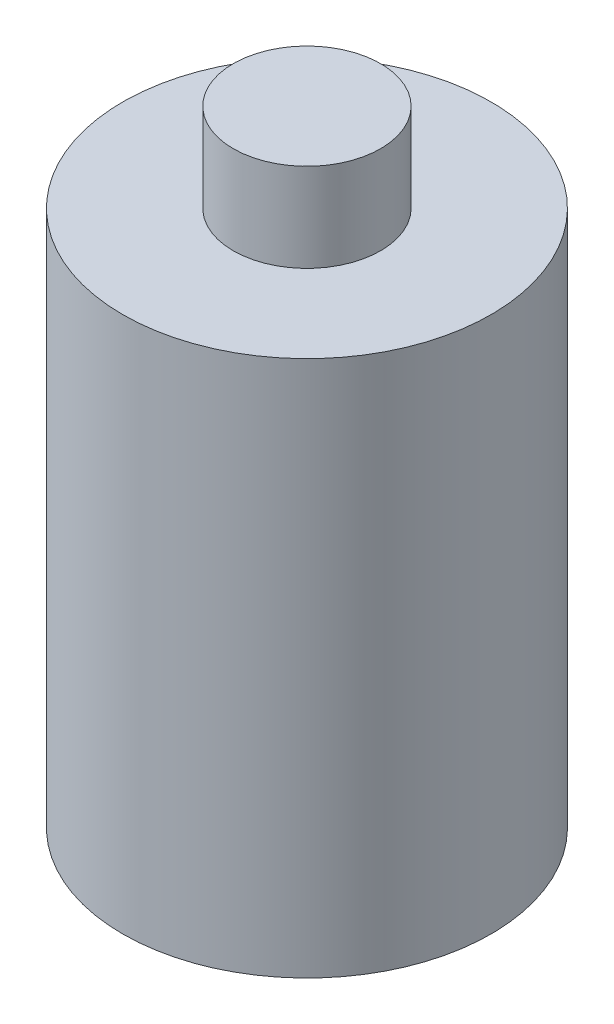
SolidWorks part; units mm, degrees
ref_plane "前视基准面" through (0, 0, 0) normal (0, 0, 1) x (1, 0, 0)
ref_plane "上视基准面" through (0, 0, 0) normal (0, 1, 0) x (1, 0, 0)
ref_plane "右视基准面" through (0, 0, 0) normal (1, 0, 0) x (0, 0, -1)
sketch "草图1" plane through (0, 0, 0) normal (0, 1, 0) x (1, 0, 0)
  circle A0 centre (0, 0) radius 6.25
  dimension "D1" = 12.5
extrude "凸台-拉伸1" add sketch "草图1" along normal blind 18.2
sketch "草图2" plane through (0, 18.2, 0) normal (0, 1, 0) x (1, 0, 0)
  circle A0 centre (0, 0) radius 2.5
  dimension "D1" = 5
extrude "凸台-拉伸2" add sketch "草图2" along normal blind 3
